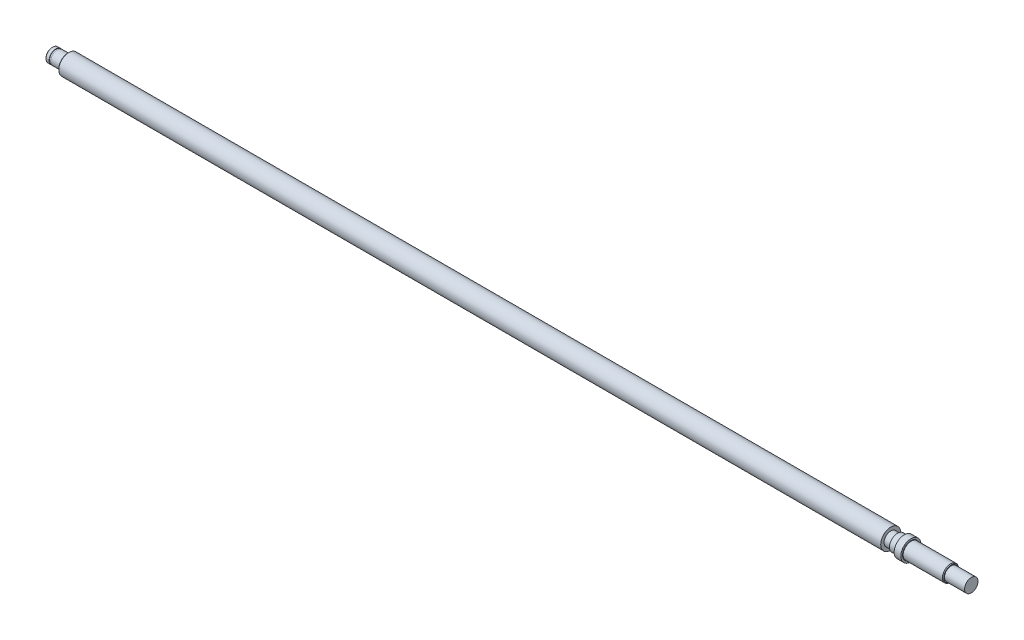
SolidWorks part; units mm, degrees
ref_plane "정면" through (0, 0, 0) normal (0, 0, 1) x (1, 0, 0)
ref_plane "윗면" through (0, 0, 0) normal (0, 1, 0) x (1, 0, 0)
ref_plane "우측면" through (0, 0, 0) normal (1, 0, 0) x (0, 0, -1)
sketch "스케치1" plane through (0, 0, 0) normal (0, 0, 1) x (1, 0, 0)
  line L0 (0, 0) -> (613, 0)
  line L1 (0, 0) -> (613, 0) construction
  line L2 (0, 0) -> (0, 7.5)
  line L3 (0, 7.5) -> (613, 7.5)
  line L4 (613, 0) -> (613, 7.5)
  dimension "D1" = 613
  dimension "D2" = 15
revolve "회전1" add sketch "스케치1" angle 360 about L1
sketch "스케치2" plane through (0, 0, 0) normal (0, 0, 1) x (1, 0, 0)
  line L0 (613, 0) -> (673.7942, 0) construction
  line L1 (613, -7.5) -> (613, 7.5) construction
  line L2 (613, 5) -> (618, 5)
  line L3 (618, 5) -> (618, 6)
  line L4 (618, 6) -> (623, 6)
  line L5 (623, 6) -> (623, 7.5)
  line L6 (623, 7.5) -> (628, 7.5)
  line L7 (628, 7.5) -> (628, 6.2)
  line L8 (628.2, 6) -> (657.5, 6)
  line L9 (658, 5.5) -> (658, 5)
  line L10 (658, 5) -> (673, 5)
  line L11 (673, 5) -> (673, 0)
  line L12 (628, 6.2) -> (628.2, 6)
  line L13 (657.5, 6) -> (658, 5.5)
  line L14 (613, 5) -> (613, 0)
  line L15 (613, 0) -> (673, 0)
  point P12 (628, 6)
  point P13 (658, 6)
  dimension "D1" = 10
  dimension "D2" = 12
  dimension "D3" = 15
  dimension "D4" = 5
  dimension "D5" = 5
  dimension "D6" = 5
  dimension "D7" = 30
  dimension "D8" = 15
revolve "회전3" add sketch "스케치2" angle 360 about L0
sketch "스케치3" plane through (0, 0, 0) normal (0, 0, 1) x (1, 0, 0)
  line L0 (0, 0) -> (-48.287, 0) construction
  line L1 (0, 5) -> (-8, 5)
  line L2 (0, 7.5) -> (0, -7.5) construction
  line L3 (-8, 5) -> (-8, 4.8)
  line L4 (-8, 4.8) -> (-9.15, 4.8)
  line L5 (-9.15, 4.8) -> (-9.15, 5)
  line L6 (-9.15, 5) -> (-12, 5)
  line L7 (-12, 5) -> (-12, 0)
  line L8 (0, 5) -> (0, 0)
  line L9 (0, 0) -> (-12, 0)
  dimension "D1" = 9.6
  dimension "D2" = 10
  dimension "D4" = 2.85
  dimension "D5" = 12
  dimension "D6" = 1.15
revolve "회전4" add sketch "스케치3" angle 360 about L0
fillet "필렛1" radius 0.3 1 edges at (0, 0, -5)
chamfer "모따기1" distance 0.5 angle 45 2 edges at (-12, 0, -5) (0, 0, 7.5)
